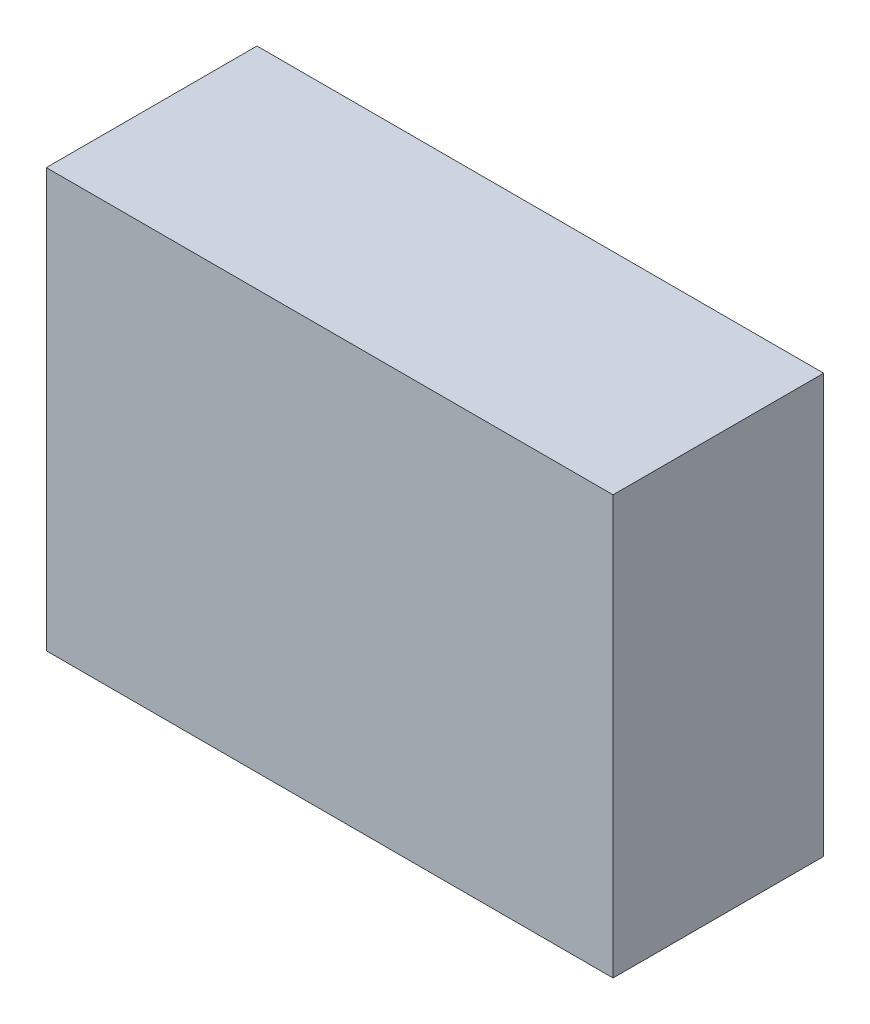
SolidWorks part; units mm, degrees
ref_plane "Front Plane" through (0, 0, 0) normal (0, 0, 1) x (1, 0, 0)
ref_plane "Top Plane" through (0, 0, 0) normal (0, 1, 0) x (1, 0, 0)
ref_plane "Right Plane" through (0, 0, 0) normal (1, 0, 0) x (0, 0, -1)
sketch "Sketch1" plane through (0, 0, 0) normal (0, 0, 1) x (1, 0, 0)
  line L1 (0, 0) -> (4.09, 0)
  line L2 (0, 0) -> (0, 3.02)
  line L3 (0, 3.02) -> (4.09, 3.02)
  line L4 (4.09, 0) -> (4.09, 3.02)
  dimension "D1" = 4.09
  dimension "D2" = 3.02
extrude "Boss-Extrude1" add sketch "Sketch1" along normal blind 1.52 contours L2 L3 L4 L1
